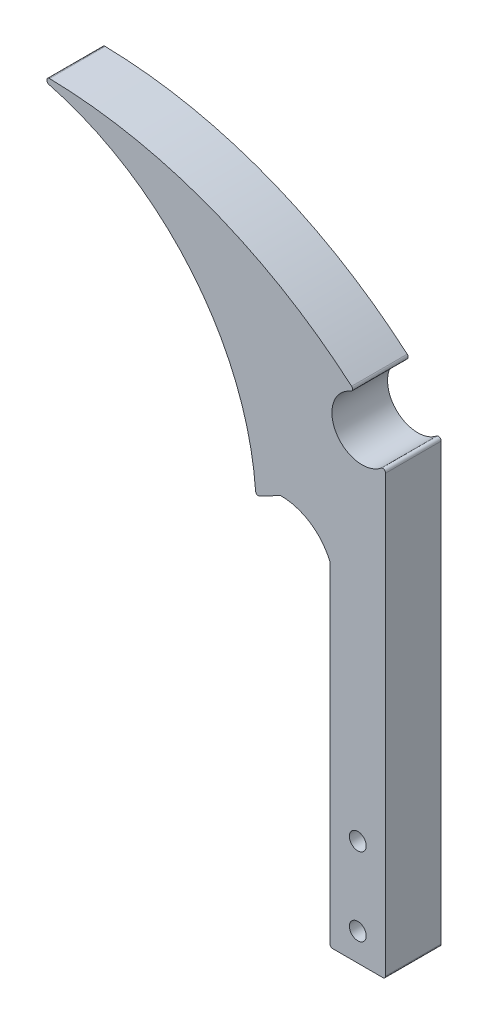
SolidWorks part; units mm, degrees
ref_plane "Front Plane" through (0, 0, 0) normal (0, 0, 1) x (1, 0, 0)
ref_plane "Top Plane" through (0, 0, 0) normal (0, 1, 0) x (1, 0, 0)
ref_plane "Right Plane" through (0, 0, 0) normal (1, 0, 0) x (0, 0, -1)
sketch "Sketch1" plane through (0, 0, 0) normal (0, 0, 1) x (1, 0, 0)
  line L13 (0, 0) -> (0, 80)
  line L14 (0, 0) -> (-10, 0)
  line L15 (-10, 0) -> (-10, 60)
  line L18 (0, 0) -> (0, 110) construction
  line L19 (0, 110) -> (-65, 110) construction
  line L20 (-18.9072, 65.8609) -> (-23.3277, 63.5245)
  arc A0 (-10, 60) -> (-18.9072, 65.8609) centre (-18.8091, 56.3111) ccw
  arc A1 (-23.3277, 63.5245) -> (-65, 110) centre (-73.247, 60.6848) ccw
  arc A3 (0, 80) -> (-5.4469, 88.6815) centre (-4.2325, 83.3939) cw
  arc A4 (-65, 110) -> (-5.4469, 88.6815) centre (-62.157, 24.1022) cw
  point P13 (-13.5595, 64.2892)
  point P14 (-33.1909, 105.0187)
  point P15 (-36.0204, 94.0641)
  dimension "D1" = 80
  dimension "D2" = 60
  dimension "D6" = 85.9448
  dimension "D7" = 83.3939
  dimension "D5" = 65
  dimension "D10" = 5
  dimension "D11" = 13.5595
  dimension "D8" = 5.4252
  dimension "D9" = 50
  dimension "D3" = 10
  dimension "D4" = 110
  dimension "D12" = 13.7859
  dimension "D13" = 65.8609
  dimension "D14" = 105.0187
  dimension "D15" = 94.0641
extrude "Boss-Extrude1" add sketch "Sketch1" along normal blind 10
fillet "Fillet1" radius 0.5 5 edges at (0, 80, 5) (-5.4469, 88.6815, 5) (-10, 60, 5) (-23.3277, 63.5245, 5) (-65, 110, 5)
sketch "Sketch2" plane through (0, 0, 10) normal (0, 0, 1) x (1, 0, 0)
  line L0 (-10, 59.8981) -> (-10, 0) construction
  line L1 (-10, 0) -> (0, 0) construction
  circle A0 centre (-5, 5) radius 1.515
  circle A1 centre (-5, 19) radius 1.515
  dimension "D1" = 3.03
  dimension "D2" = 3.03
  dimension "D3" = 14
  dimension "D4" = 5
  dimension "D5" = 5
  dimension "D6" = 19
extrude "Cut-Extrude1" cut sketch "Sketch2" against normal through all
fillet "Fillet2" radius 0.5 2 edges at (0, 0, 5) (-10, 0, 5)
